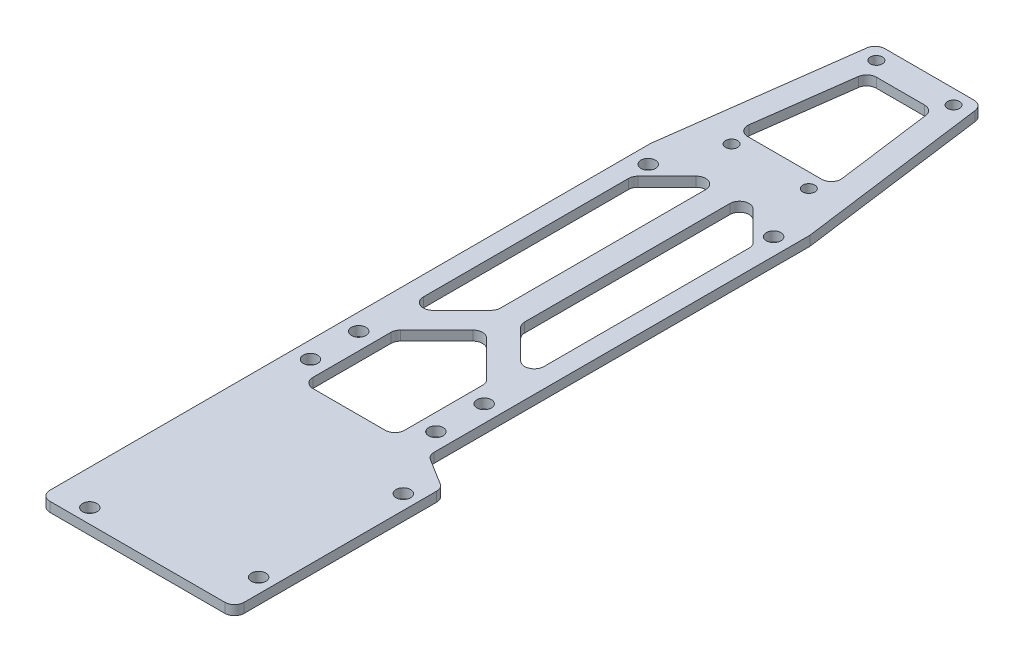
SolidWorks part; units mm, degrees
material "Thornel Mat VMA"
ref_plane "前视基准面" through (0, 0, 0) normal (0, 0, 1) x (1, 0, 0)
ref_plane "上视基准面" through (0, 0, 0) normal (0, 1, 0) x (1, 0, 0)
ref_plane "右视基准面" through (0, 0, 0) normal (1, 0, 0) x (0, 0, -1)
sketch "草图1" plane through (0, 0, 0) normal (0, 1, 0) x (1, 0, 0)
  line L0 (0, -120.3) -> (0, 0) construction
  line L1 (11, 0) -> (-11, 0)
  line L2 (-11, 0) -> (-16.5, -41.3)
  line L3 (-16.5, -41.3) -> (-16.5, -120.3)
  line L4 (-16.5, -120.3) -> (16.5, -120.3) construction
  line L5 (16.5, -41.3) -> (16.5, -120.3)
  line L6 (11, 0) -> (16.5, -41.3)
  line L7 (-8, -3) -> (-8, -33) construction
  line L8 (-16.5, -41.3) -> (0, -41.3) construction
  line L9 (-13, -45.3) -> (-13, -105.3) construction
  line L10 (-13, -105.3) -> (-13, -115.3) construction
  line L11 (16.5, -120.3) -> (23.75, -124.8)
  line L12 (23.75, -124.8) -> (23.75, -167.8)
  line L16 (0, -120.3) -> (0, -144.8) construction
  line L17 (0, -144.8) -> (23.75, -144.8) construction
  line L18 (-16.5, -120.3) -> (-16.5, -167.8)
  line L19 (-16.5, -167.8) -> (23.75, -167.8)
  circle A0 centre (-8, -3) radius 1.25
  circle A1 centre (-8, -33) radius 1.25
  circle A2 centre (8, -33) radius 1.25
  circle A3 centre (8, -3) radius 1.25
  circle A4 centre (-13, -45.3) radius 1.5
  circle A5 centre (-13, -105.3) radius 1.5
  circle A6 centre (-13, -115.3) radius 1.5
  circle A7 centre (13, -115.3) radius 1.5
  circle A8 centre (13, -105.3) radius 1.5
  circle A9 centre (13, -45.3) radius 1.5
  circle A10 centre (20.75, -129.8) radius 1.5
  circle A11 centre (20.75, -159.8) radius 1.5
  circle A12 centre (-9.25, -164.8) radius 1.5
  dimension "D2" = 2.5
  dimension "D3" = 8.3
  dimension "D5" = 16
  dimension "D6" = 3
  dimension "D7" = 3
  dimension "D10" = 4
  dimension "D11" = 3
  dimension "D12" = 26
  dimension "D13" = 5
  dimension "D17" = 3
  dimension "D18" = 30
  dimension "D19" = 3
  dimension "D20" = 3
  dimension "D21" = 5
  dimension "D22" = 30
  dimension "D1" = 33
  dimension "D4" = 30
  dimension "D8" = 79
  dimension "D9" = 10
  dimension "D14" = 24.5
  dimension "D15" = 23.75
  dimension "D16" = 20
  dimension "D23" = 3
extrude "凸台-拉伸1" add sketch "草图1" along normal blind 2
sketch "草图2" plane through (0, 2, 0) normal (0, 1, 0) x (1, 0, 0)
  line L0 (0, 0) -> (0, -167.8) construction
  line L1 (-16.5, -167.8) -> (23.75, -167.8) construction
  line L2 (6.7549, -6) -> (-6.7549, -6)
  line L3 (-6.7549, -6) -> (-9.951, -30)
  line L4 (-9.951, -30) -> (9.951, -30)
  line L5 (6.7549, -6) -> (9.951, -30)
  line L6 (11, 0) -> (-11, 0) construction
  line L7 (16.5, -41.3) -> (11, 0) construction
  line L8 (12.5, -97.2289) -> (2.5, -87.2289)
  line L9 (-12.5, -49.0426) -> (-2.5, -39.0426)
  line L10 (-12.5, -49.0426) -> (-12.5, -97.2289)
  line L11 (-12.5, -97.2289) -> (-2.5, -87.2289)
  line L12 (-2.5, -39.0426) -> (-2.5, -87.2289)
  line L13 (2.5, -39.0426) -> (2.5, -87.2289)
  line L14 (12.5, -49.0426) -> (2.5, -39.0426)
  line L15 (12.5, -49.0426) -> (12.5, -97.2289)
  line L16 (-16.5, -41.3) -> (-16.5, -167.8) construction
  line L17 (-9.5, -101.3) -> (0, -91.8)
  line L19 (-9.5, -101.3) -> (-9.5, -120.3)
  line L20 (-9.5, -120.3) -> (9.5, -120.3)
  line L21 (9.5, -101.3) -> (9.5, -120.3)
  line L23 (9.5, -101.3) -> (0, -91.8)
  line L24 (16.5, -120.3) -> (16.5, -41.3) construction
  circle A0 centre (8, -33) radius 1.25 construction
  circle A2 centre (-13, -45.3) radius 1.5 construction
  circle A3 centre (13, -105.3) radius 1.5 construction
  circle A4 centre (13, -115.3) radius 1.5 construction
  point P10 (0, -30)
  point P11 (0, -6)
  dimension "D9" = 3
  dimension "D1" = 6
  dimension "D2" = 5
  dimension "D3" = 3
  dimension "D4" = 4
  dimension "D5" = 45
  dimension "D6" = 5
  dimension "D7" = 7
  dimension "D8" = 5
  dimension "D10" = 45
  dimension "D11" = 4
  dimension "D12" = 5
extrude "切除-拉伸1" cut sketch "草图2" against normal blind 10
fillet "圆角1" radius 2 23 edges at (-16.5, 1, 167.8) (23.75, 1, 167.8) (23.75, 1, 124.8) (16.5, 1, 120.3) (-9.5, 1, 120.3) (9.5, 1, 120.3) (12.5, 1, 97.2289) (2.5, 1, 87.2289) (-2.5, 1, 87.2289) (-12.5, 1, 97.2289) (-9.5, 1, 101.3) (9.5, 1, 101.3) (0, 1, 91.8) (12.5, 1, 49.0426) (-12.5, 1, 49.0426) (-2.5, 1, 39.0426) (2.5, 1, 39.0426) (9.951, 1, 30) (-9.951, 1, 30) (6.7549, 1, 6) (-6.7549, 1, 6) (11, 1, 0) (-11, 1, 0)
